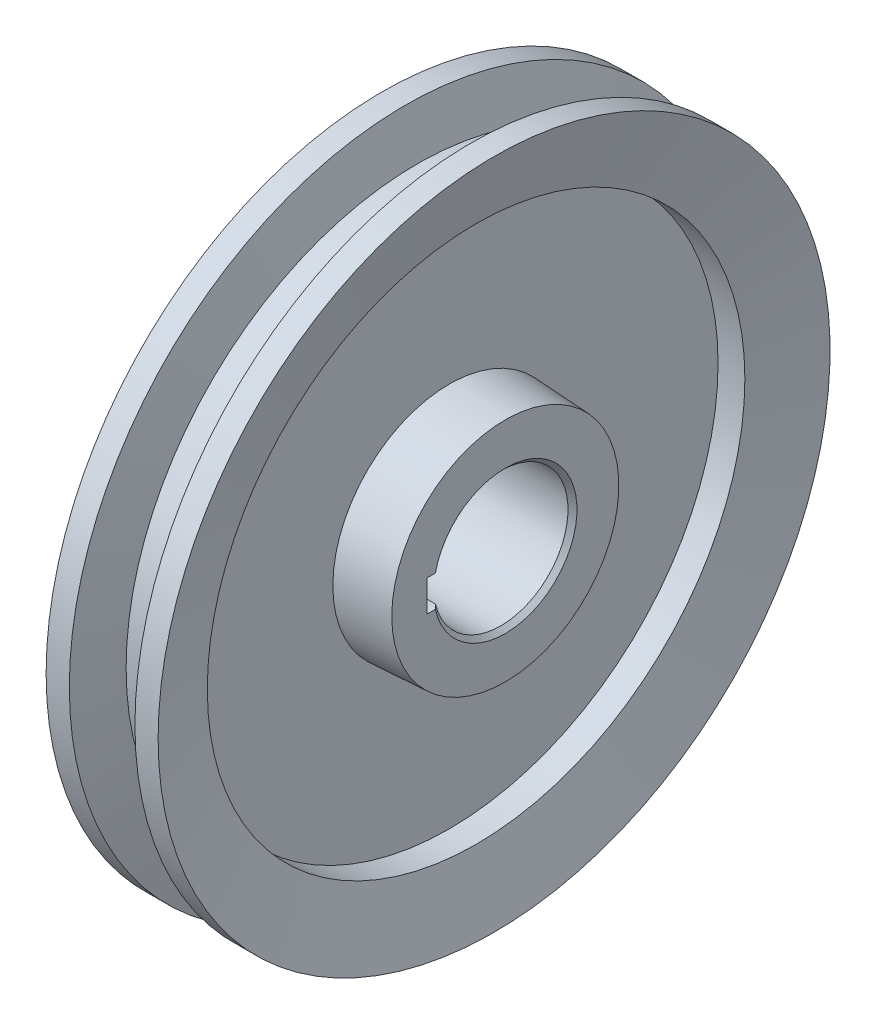
SolidWorks part; units mm, degrees
ref_plane "Front Plane" through (0, 0, 0) normal (0, 0, 1) x (1, 0, 0)
ref_plane "Top Plane" through (0, 0, 0) normal (0, 1, 0) x (1, 0, 0)
ref_plane "Right Plane" through (0, 0, 0) normal (1, 0, 0) x (0, 0, -1)
sketch "Sketch1" plane through (0, 0, 0) normal (0, 0, 1) x (1, 0, 0)
  line L0 (0, 96.8622) -> (0, 0) construction
  line L1 (0, 0) -> (144.2467, 0) construction
  line L2 (15, 15) -> (15, 25.3449)
  line L3 (15, 25.3449) -> (2.5, 26)
  line L4 (2.5, 26) -> (2.5, 60)
  line L5 (2.5, 60) -> (8.4808, 60)
  line L6 (8.4808, 60) -> (12.5, 75)
  line L7 (-15, 15) -> (-15, 25.3449)
  line L8 (-15, 25.3449) -> (-2.5, 26)
  line L9 (-2.5, 26) -> (-2.5, 60)
  line L10 (-2.5, 60) -> (-8.4808, 60)
  line L11 (-8.4808, 60) -> (-12.5, 75)
  line L12 (-12.5, 75) -> (-7.3236, 75)
  line L13 (-15, 15) -> (15, 15)
  line L14 (-7.3236, 75) -> (-4.6441, 65)
  line L15 (-4.6441, 65) -> (4.6441, 65)
  line L16 (4.6441, 65) -> (7.3236, 75)
  line L18 (7.3236, 75) -> (12.5, 75)
  point P12 (0, 0)
  point P15 (0, 0)
  point P16 (0, 0)
  point P17 (0, 0)
  point P18 (0, 0)
  point P19 (0, 91.4884)
  point P20 (0, 81.6838)
  point P21 (0, 103.1546)
  point P28 (0, 96.8622)
  point P29 (-7.3236, 52.4399)
  point P30 (0, 0)
  point P31 (-2.5, 26)
  point P32 (2.5, 26)
  point P33 (15, 15)
  point P34 (-2.5, 56.5899)
  point P35 (-7.3236, 70.3655)
  point P36 (-7.3236, 75)
  point P37 (-8.4808, 60)
  point P38 (-2.5, 60)
  point P39 (8.4808, 60)
  point P40 (2.5, 60)
  point P41 (12.5, 75)
  point P42 (7.3236, 75)
  dimension "D1" = 30
  dimension "D2" = 5
  dimension "D3" = 5
  dimension "D4" = 30
  dimension "D5" = 25
  dimension "D6" = 5
  dimension "D7" = 15
  dimension "D8" = 26
  dimension "D9" = 3
  dimension "D10" = 65
  dimension "D11" = 75
  dimension "D12" = 60
revolve "Revolve1" add sketch "Sketch1" angle 360 about L1
sketch "Sketch2" plane through (15, 0, 0) normal (1, 0, 0) x (0, 0, -1)
  line L0 (-14.586, 3.5) -> (-17.5, 3.5)
  line L1 (-17.5, 3.5) -> (-17.5, -3.5)
  line L2 (-17.5, -3.5) -> (-14.586, -3.5)
  line L3 (0, 0) -> (-43.3327, 0) construction
  circle A1 centre (0, 0) radius 15 construction
  circle A3 centre (0, 0) radius 15
  arc A4 (-14.586, -3.5) -> (-14.586, 3.5) centre (0, 0) ccw
  point P9 (-17.5, 0)
  dimension "D2" = 32.5
  dimension "D1" = 7
  dimension "D3" = 0
extrude "Cut-Extrude1" cut sketch "Sketch2" against normal blind 30
chamfer "Chamfer1" distance 1 angle 45 1 edges at (15, 0, -15)
chamfer "Chamfer2" distance 1 angle 45 1 edges at (-15, 0, -15)
